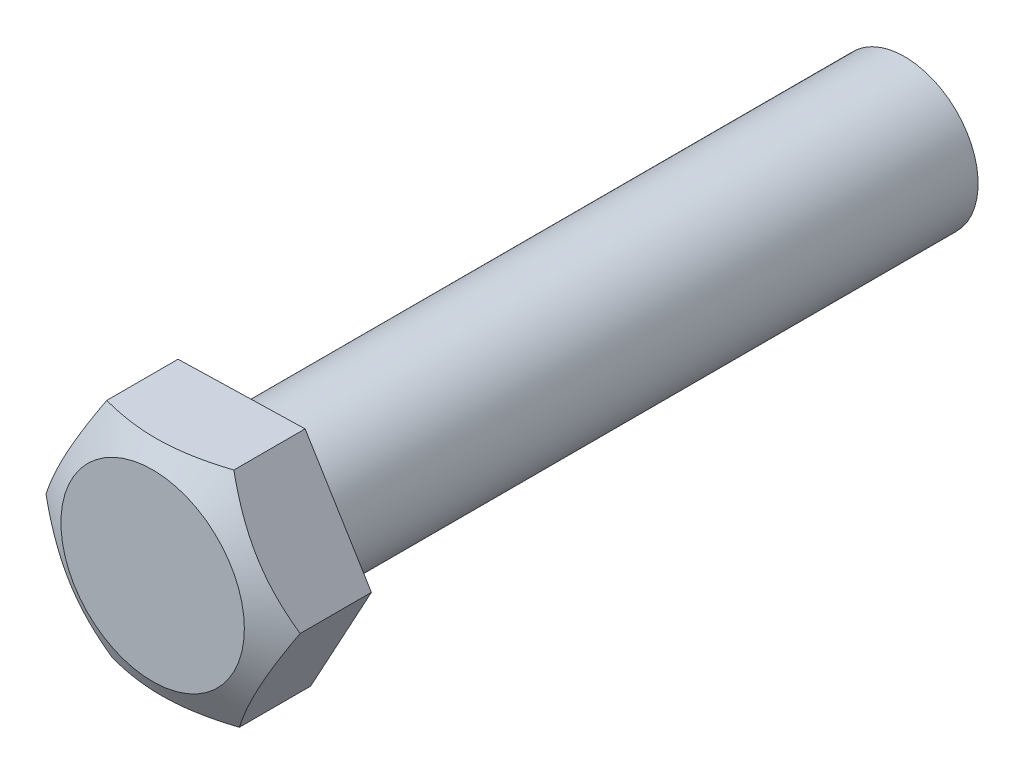
SolidWorks part; units mm, degrees
ref_plane "Front Plane" through (0, 0, 0) normal (0, 0, 1) x (1, 0, 0)
ref_plane "Top Plane" through (0, 0, 0) normal (0, 1, 0) x (1, 0, 0)
ref_plane "Right Plane" through (0, 0, 0) normal (1, 0, 0) x (0, 0, -1)
sketch "Sketch1" plane through (0, 0, 0) normal (0, 0, 1) x (1, 0, 0)
  circle A0 centre (0, 0) radius 10
  dimension "D1" = 20
extrude "Boss-Extrude1" add sketch "Sketch1" along normal blind 90
sketch "Sketch3" plane through (0, 0, 90) normal (0, 0, 1) x (1, 0, 0)
  line L1 (8.2805, 15.2129) -> (-9.0345, 14.7776)
  line L2 (-9.0345, 14.7776) -> (-17.315, -0.4354)
  line L3 (-17.315, -0.4354) -> (-8.2805, -15.2129)
  line L4 (-8.2805, -15.2129) -> (9.0345, -14.7776)
  line L5 (9.0345, -14.7776) -> (17.315, 0.4354)
  line L6 (17.315, 0.4354) -> (8.2805, 15.2129)
  circle A0 centre (0, 0) radius 15 construction
  dimension "D1" = 30
extrude "Boss-Extrude2" add sketch "Sketch3" along normal blind 12.5
sketch "Sketch4" plane through (0, 0, 102.5) normal (0, 0, 1) x (1, 0, 0)
  circle A0 centre (0, 0) radius 12.5
extrude "Cut-Extrude2" cut sketch "Sketch4" against normal blind 5 draft 60 flip side to cut
